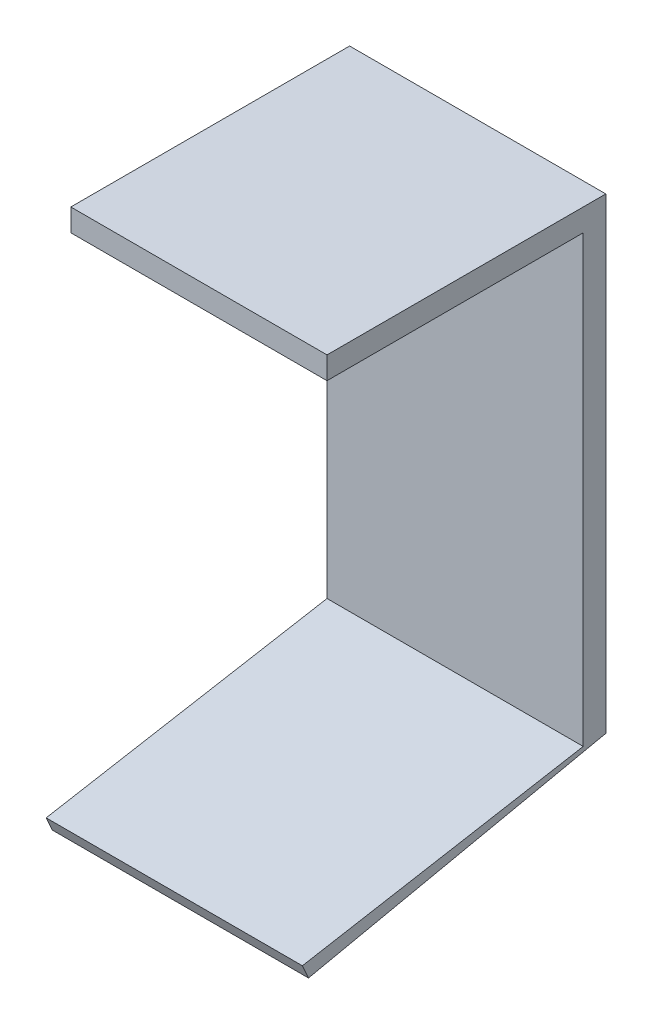
SolidWorks part; units mm, degrees
ref_plane "Front Plane" through (0, 0, 0) normal (0, 0, 1) x (1, 0, 0)
ref_plane "Top Plane" through (0, 0, 0) normal (0, 1, 0) x (1, 0, 0)
ref_plane "Right Plane" through (0, 0, 0) normal (1, 0, 0) x (0, 0, -1)
sketch "Sketch1" plane through (0, 0, 0) normal (0, 1, 0) x (1, 0, 0)
  line L1 (0, 0) -> (68, 0)
  line L2 (0, 0) -> (0, 6)
  line L3 (0, 6) -> (68, 6)
  line L4 (68, 0) -> (68, 6)
  dimension "D1" = 68
  dimension "D2" = 6
extrude "Boss-Extrude1" add sketch "Sketch1" along normal blind 124
sketch "Sketch3" plane through (0, 0, 0) normal (1, 0, 0) x (0, 0, -1)
  line L0 (0, 0) -> (-74.5366, -13.1428)
  line L1 (-72.9112, -16.7731) -> (-74.5366, -13.1428)
  line L2 (0, 0) -> (6, 0)
  line L3 (6, 0) -> (-72.9112, -16.7731)
  dimension "D1" = 170
  dimension "D2" = 168
extrude "Boss-Extrude2" add sketch "Sketch3" along normal blind 68
sketch "Sketch4" plane through (0, 0, 0) normal (0, 0, 1) x (1, 0, 0)
  line L0 (68, 124) -> (68, 0) construction
  line L1 (68, 118.0636) -> (0, 118.0636)
  line L2 (68, 118.0636) -> (68, 124)
  line L3 (68, 124) -> (0, 124)
  line L4 (0, 118.0636) -> (0, 124)
extrude "Boss-Extrude3" add sketch "Sketch4" along normal blind 68
